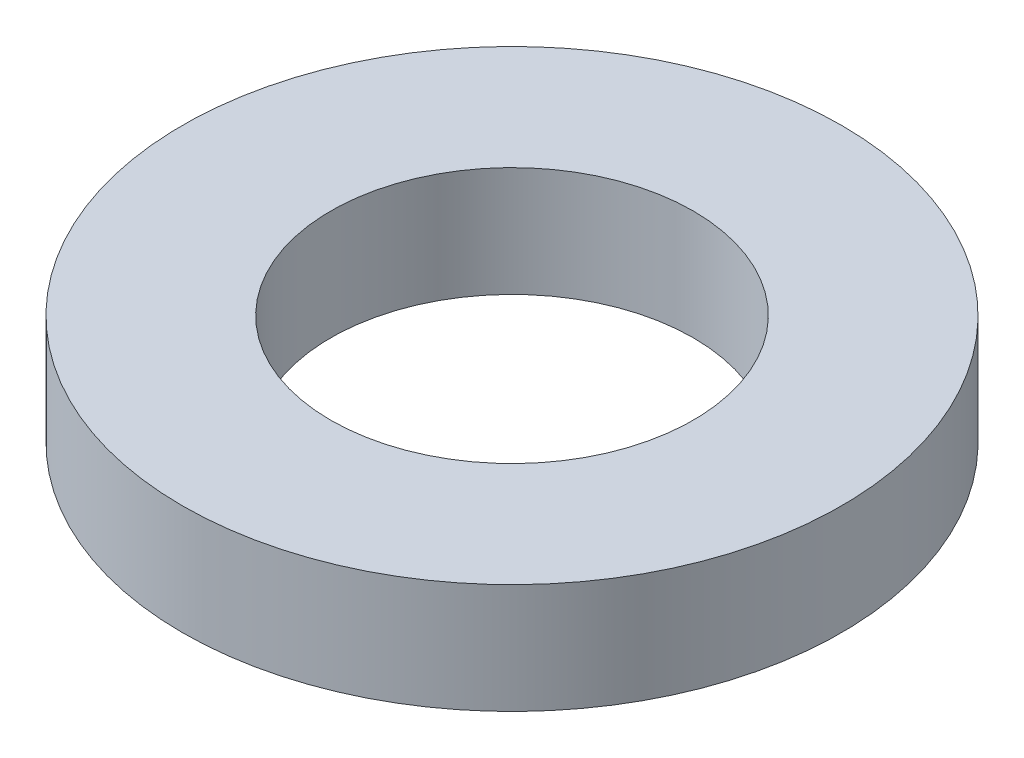
SolidWorks part; units mm, degrees
ref_plane "前视基准面" through (0, 0, 0) normal (0, 0, 1) x (1, 0, 0)
ref_plane "上视基准面" through (0, 0, 0) normal (0, 1, 0) x (1, 0, 0)
ref_plane "右视基准面" through (0, 0, 0) normal (1, 0, 0) x (0, 0, -1)
sketch "草图1" plane through (0, 0, 0) normal (0, 1, 0) x (1, 0, 0)
  circle A0 centre (0, 0) radius 1.65
  circle A1 centre (0, 0) radius 3
  dimension "D1" = 3.3
  dimension "D2" = 6
extrude "凸台-拉伸1" add sketch "草图1" along normal blind 1
